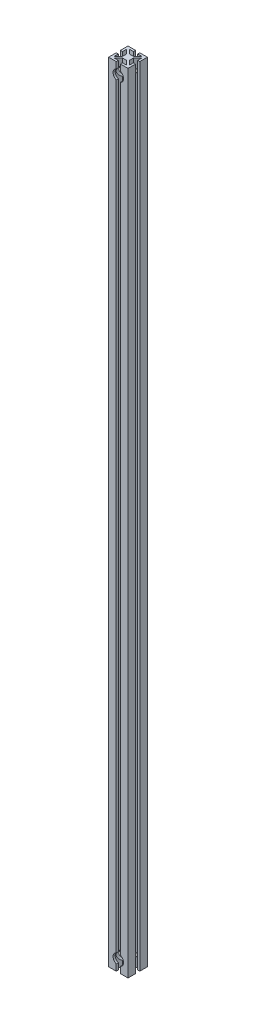
SolidWorks part; units mm, degrees
ref_plane "Front Plane" through (0, 0, 0) normal (0, 0, 1) x (1, 0, 0)
ref_plane "Top Plane" through (0, 0, 0) normal (0, 1, 0) x (1, 0, 0)
ref_plane "Right Plane" through (0, 0, 0) normal (1, 0, 0) x (0, 0, -1)
sketch "Sketch2" plane through (0.5947, 0, 0.5947) normal (0, 1, 0) x (1, 0, 0)
  line L0 (-0.5947, 0.5947) -> (-0.5947, 20.2394) construction
  line L1 (-0.5947, 0.5947) -> (-20.2394, 0.5947) construction
  line L2 (-0.5947, 0.5947) -> (-20.2394, 20.2394) construction
  line L3 (-19.6447, 19.6447) -> (-4.6587, 19.6447)
  line L4 (-4.6587, 19.6447) -> (-4.6587, 15.5807)
  line L5 (-4.6587, 15.5807) -> (-12.707, 15.5807)
  line L6 (-12.707, 15.5807) -> (-4.4774, 7.3511)
  line L7 (-4.4774, 7.3511) -> (3.288, 7.3511)
  line L8 (-19.6447, 19.6447) -> (-19.6447, 4.6587)
  line L9 (-19.6447, 4.6587) -> (-15.5807, 4.6587)
  line L10 (-15.5807, 4.6587) -> (-15.5807, 12.707)
  line L11 (-15.5807, 12.707) -> (-7.3511, 4.4774)
  line L12 (-7.3511, 4.4774) -> (-7.3511, -3.288)
  line L13 (-4.4774, -6.1617) -> (3.288, -6.1617)
  line L14 (-12.707, -14.3913) -> (-4.4774, -6.1617)
  line L15 (-4.6587, -14.3913) -> (-12.707, -14.3913)
  line L16 (-4.6587, -18.4553) -> (-4.6587, -14.3913)
  line L17 (-19.6447, -18.4553) -> (-4.6587, -18.4553)
  line L18 (-19.6447, -18.4553) -> (-19.6447, -3.4693)
  line L19 (-19.6447, -3.4693) -> (-15.5807, -3.4693)
  line L20 (-15.5807, -3.4693) -> (-15.5807, -11.5176)
  line L21 (-15.5807, -11.5176) -> (-7.3511, -3.288)
  line L22 (11.5176, 15.5807) -> (3.288, 7.3511)
  line L23 (3.4693, 15.5807) -> (11.5176, 15.5807)
  line L24 (3.4693, 19.6447) -> (3.4693, 15.5807)
  line L25 (18.4553, 19.6447) -> (3.4693, 19.6447)
  line L26 (18.4553, 19.6447) -> (18.4553, 4.6587)
  line L27 (18.4553, 4.6587) -> (14.3913, 4.6587)
  line L28 (14.3913, 4.6587) -> (14.3913, 12.707)
  line L29 (14.3913, 12.707) -> (6.1617, 4.4774)
  line L30 (6.1617, 4.4774) -> (6.1617, -3.288)
  line L31 (14.3913, -11.5176) -> (6.1617, -3.288)
  line L32 (14.3913, -3.4693) -> (14.3913, -11.5176)
  line L33 (18.4553, -3.4693) -> (14.3913, -3.4693)
  line L34 (18.4553, -18.4553) -> (18.4553, -3.4693)
  line L35 (18.4553, -18.4553) -> (3.4693, -18.4553)
  line L36 (3.4693, -18.4553) -> (3.4693, -14.3913)
  line L37 (3.4693, -14.3913) -> (11.5176, -14.3913)
  line L38 (11.5176, -14.3913) -> (3.288, -6.1617)
  point P26 (-7.3511, 0.5947)
  point P27 (-0.5947, 7.3511)
  point P44 (-0.5947, -6.1617)
  dimension "D1" = 38.1
  dimension "D2" = 8.128
  dimension "D3" = 13.5128
  dimension "D4" = 4.064
  dimension "D5" = 4.064
extrude "Boss-Extrude1" add sketch "Sketch2" along normal blind 1549.4
other "1515<1>"
sketch "Sketch3" plane through (0, 0, 19.05) normal (0, 0, 1) x (1, 0, 0)
  line L0 (4.064, 0) -> (19.05, 0) construction
  circle A0 centre (0, 21.844) radius 10.287
  dimension "D2" = 20.574
  dimension "D1" = 21.844
extrude "Cut-Extrude1" cut sketch "Sketch3" against normal blind 16.51
mirror "Mirror1" about plane through (0, 0, 0) normal (0, 0, 1) of "Cut-Extrude1"
ref_plane "midplane" through (0, 774.7, 0) normal (0, -1, 0) x (1, 0, 0)
mirror "Mirror2" about plane through (0, 774.7, 0) normal (0, -1, 0) of "Mirror1", "Cut-Extrude1"
